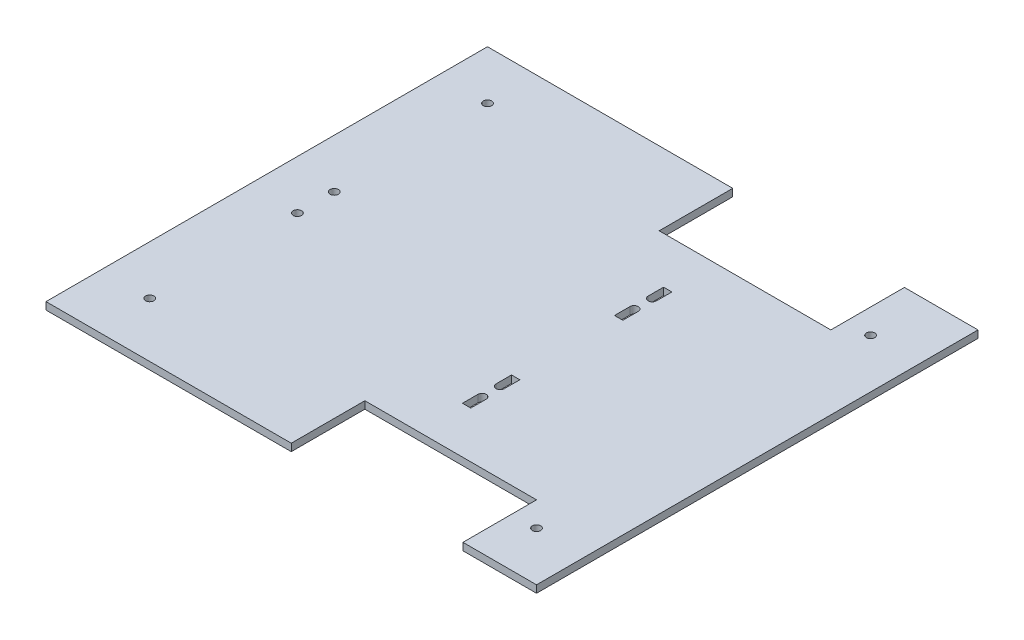
SolidWorks part; units mm, degrees
ref_plane "Front Plane" through (0, 0, 0) normal (0, 0, 1) x (1, 0, 0)
ref_plane "Top Plane" through (0, 0, 0) normal (0, 1, 0) x (1, 0, 0)
ref_plane "Right Plane" through (0, 0, 0) normal (1, 0, 0) x (0, 0, -1)
sketch "Sketch1" plane through (0, 0, 0) normal (0, 1, 0) x (1, 0, 0)
  line L0 (-48.9431, 29.6359) -> (1729.0569, 29.6359)
  line L1 (1729.0569, 29.6359) -> (1729.0569, -732.3641)
  line L2 (-48.9431, 29.6359) -> (-48.9431, -732.3641)
  line L3 (1729.0569, -732.3641) -> (2491.0569, -732.3641)
  line L4 (2491.0569, -732.3641) -> (2491.0569, 3839.6359)
  line L5 (2491.0569, 3839.6359) -> (1729.0569, 3839.6359)
  line L6 (1729.0569, 3839.6359) -> (1729.0569, 3077.6359)
  line L7 (1729.0569, 3077.6359) -> (-48.9431, 3077.6359)
  line L8 (-48.9431, 3077.6359) -> (-48.9431, 3839.6359)
  line L9 (-48.9431, 3839.6359) -> (-2588.9431, 3839.6359)
  line L10 (-2588.9431, 3839.6359) -> (-2588.9431, -732.3641)
  line L11 (-2588.9431, -732.3641) -> (-48.9431, -732.3641)
  line L19 (565.7369, 2435.0159) -> (565.7369, 2595.0359)
  line L20 (565.7369, 2595.0359) -> (479.3769, 2595.0359)
  line L21 (479.3769, 2595.0359) -> (479.3769, 2435.0159)
  line L23 (565.7369, 2247.0559) -> (565.7369, 2087.0359)
  line L24 (565.7369, 2087.0359) -> (479.3769, 2087.0359)
  line L25 (479.3769, 2087.0359) -> (479.3769, 2247.0559)
  line L26 (479.3769, 1020.2359) -> (479.3769, 860.2159)
  line L27 (565.7369, 1020.2359) -> (479.3769, 1020.2359)
  line L28 (565.7369, 860.2159) -> (565.7369, 1020.2359)
  line L30 (479.3769, 512.2359) -> (479.3769, 672.2559)
  line L31 (565.7369, 512.2359) -> (479.3769, 512.2359)
  line L32 (565.7369, 672.2559) -> (565.7369, 512.2359)
  circle A0 centre (-2080.9431, -166.5082) radius 43.18
  circle A1 centre (-2080.9431, 1744.1359) radius 43.18
  circle A2 centre (-2080.9431, 1363.1359) radius 43.18
  arc A3 (479.3769, 2435.0159) -> (565.7369, 2435.0159) centre (522.5569, 2435.0159) ccw
  arc A4 (565.7369, 2247.0559) -> (479.3769, 2247.0559) centre (522.5569, 2247.0559) ccw
  arc A5 (565.7369, 860.2159) -> (479.3769, 860.2159) centre (522.5569, 860.2159) cw
  arc A6 (479.3769, 672.2559) -> (565.7369, 672.2559) centre (522.5569, 672.2559) cw
  circle A7 centre (-2080.9431, 3331.6359) radius 43.18
  circle A8 centre (1983.0569, -224.3641) radius 43.18
  circle A9 centre (1983.0569, 3235.0991) radius 43.18
extrude "Boss-Extrude1" add sketch "Sketch1" along normal blind 76.2
